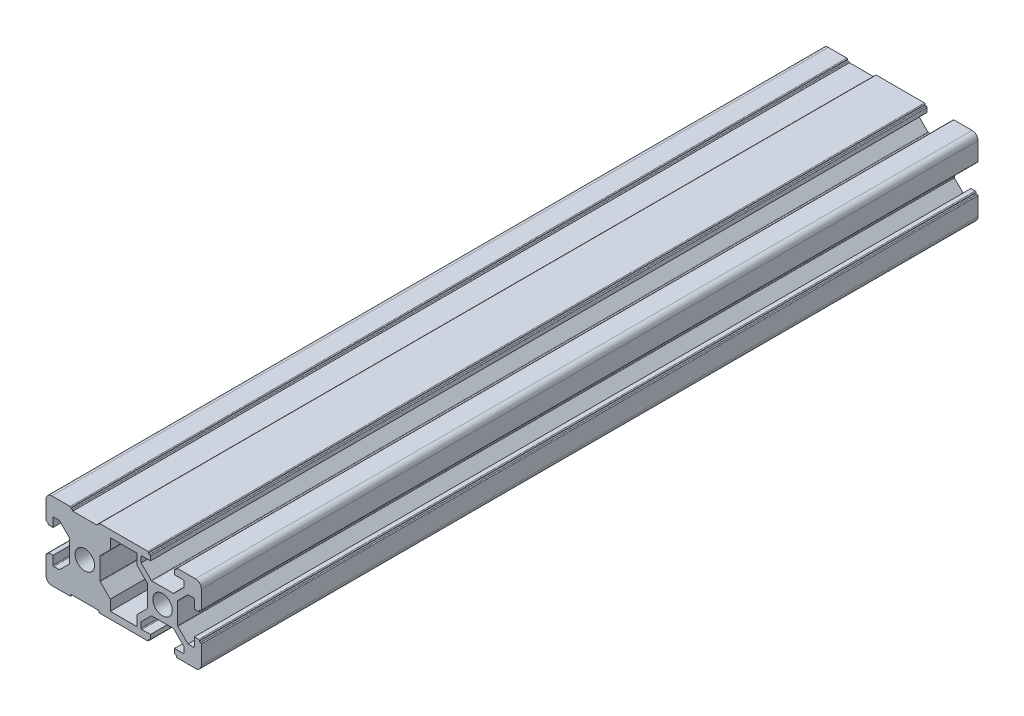
SolidWorks part; units mm, degrees
ref_plane "前视基准面" through (0, 0, 0) normal (0, 0, 1) x (1, 0, 0)
ref_plane "上视基准面" through (0, 0, 0) normal (0, 1, 0) x (1, 0, 0)
ref_plane "右视基准面" through (0, 0, 0) normal (1, 0, 0) x (0, 0, -1)
sketch "Sketch1" plane through (0, 0, 0) normal (0, 0, 1) x (1, 0, 0)
  line L0 (-8.5, 10) -> (-3.8, 10)
  line L3 (-8.5, -10) -> (-3.8, -10)
  line L5 (-10, 8.5) -> (-10, 3.8)
  line L10 (3.9, 2.7565) -> (3.9, -2.7565)
  line L11 (-3.9, 2.7565) -> (-3.9, -2.7565)
  line L12 (-3.9586, -2.8979) -> (-6.5607, -5.5)
  line L13 (3.6, 9.7) -> (3.6, 9.8)
  line L21 (-3.4, -9.5) -> (-3.3, -9.5)
  line L22 (3.8, -10) -> (8.5, -10)
  line L23 (3.3, -9.5) -> (3.4, -9.5)
  line L24 (-3.6, -9.7) -> (-3.6, -9.8)
  line L25 (3.6, -9.7) -> (3.6, -9.8)
  line L26 (-6.5607, -5.5) -> (-8, -5.5)
  line L27 (-9.7, -3.6) -> (-9.8, -3.6)
  line L28 (-9.5, -3.4) -> (-9.5, -3.3)
  line L29 (-8.2, -3.1) -> (-9.3, -3.1)
  line L30 (-8.2, -5.3) -> (-8.2, -3.1)
  line L31 (-10, -3.8) -> (-10, -8.5)
  line L33 (3.8, 10) -> (8.5, 10)
  line L40 (3.9586, -2.8979) -> (6.5607, -5.5)
  line L41 (3.3, 9.5) -> (3.4, 9.5)
  line L42 (30, 8.5) -> (30, 3.8)
  line L52 (3.9586, 2.8979) -> (6.5607, 5.5)
  line L53 (-3.6, 9.7) -> (-3.6, 9.8)
  line L54 (-3.4, 9.5) -> (-3.3, 9.5)
  line L59 (-9.5, 3.4) -> (-9.5, 3.3)
  line L60 (-9.7, 3.6) -> (-9.8, 3.6)
  line L61 (-8.2, 3.1) -> (-9.3, 3.1)
  line L62 (-8.2, 5.3) -> (-8.2, 3.1)
  line L63 (-6.5607, 5.5) -> (-8, 5.5)
  line L64 (-3.9586, 2.8979) -> (-6.5607, 5.5)
  line L65 (29.7, 3.6) -> (29.8, 3.6)
  line L66 (29.5, 3.4) -> (29.5, 3.3)
  line L67 (28.2, 3.1) -> (29.3, 3.1)
  line L68 (28.2, 5.3) -> (28.2, 3.1)
  line L69 (26.5607, 5.5) -> (28, 5.5)
  line L70 (23.9586, 2.8979) -> (26.5607, 5.5)
  line L71 (23.9, 2.7565) -> (23.9, -2.7565)
  line L72 (23.9586, -2.8979) -> (26.5607, -5.5)
  line L73 (26.5607, -5.5) -> (28, -5.5)
  line L74 (28.2, -5.3) -> (28.2, -3.1)
  line L75 (28.2, -3.1) -> (29.3, -3.1)
  line L76 (29.5, -3.4) -> (29.5, -3.3)
  line L77 (29.7, -3.6) -> (29.8, -3.6)
  line L78 (30, -3.8) -> (30, -8.5)
  line L79 (28.5, -10) -> (23.8, -10)
  line L80 (23.6, -9.7) -> (23.6, -9.8)
  line L81 (23.4, -9.5) -> (23.3, -9.5)
  line L82 (23.1, -8.2) -> (23.1, -9.3)
  line L83 (25.3, -8.2) -> (23.1, -8.2)
  line L84 (25.5, -6.5607) -> (25.5, -8)
  line L85 (22.8979, -3.9586) -> (25.5, -6.5607)
  line L86 (22.7565, -3.9) -> (17.2435, -3.9)
  line L87 (17.1021, -3.9586) -> (14.5, -6.5607)
  line L88 (14.5, -6.5607) -> (14.5, -8)
  line L89 (16.9, -8.2) -> (14.7, -8.2)
  line L90 (16.9, -8.2) -> (16.9, -9.3)
  line L91 (16.7, -9.5) -> (16.6, -9.5)
  line L92 (16.4, -9.7) -> (16.4, -9.8)
  line L93 (16.2, -10) -> (11.5, -10)
  line L94 (13.4393, 5.5) -> (13.4393, 8.2)
  line L96 (6.5607, 5.5) -> (6.5607, 8.2)
  line L97 (6.5607, 8.2) -> (13.4393, 8.2)
  line L99 (16.0414, -2.8979) -> (13.4393, -5.5)
  line L100 (16.1, 2.7565) -> (16.1, -2.7565)
  line L101 (16.0414, 2.8979) -> (13.4393, 5.5)
  line L107 (16.2, 10) -> (11.5, 10)
  line L108 (16.4, 9.7) -> (16.4, 9.8)
  line L109 (16.7, 9.5) -> (16.6, 9.5)
  line L110 (16.9, 8.2) -> (16.9, 9.3)
  line L111 (16.9, 8.2) -> (14.7, 8.2)
  line L112 (14.5, 6.5607) -> (14.5, 8)
  line L113 (17.1021, 3.9586) -> (14.5, 6.5607)
  line L114 (22.7565, 3.9) -> (17.2435, 3.9)
  line L115 (22.8979, 3.9586) -> (25.5, 6.5607)
  line L116 (25.5, 6.5607) -> (25.5, 8)
  line L117 (25.3, 8.2) -> (23.1, 8.2)
  line L118 (23.1, 8.2) -> (23.1, 9.3)
  line L119 (23.4, 9.5) -> (23.3, 9.5)
  line L120 (23.6, 9.7) -> (23.6, 9.8)
  line L121 (28.5, 10) -> (23.8, 10)
  line L122 (13.4393, -5.5) -> (13.4393, -8.2)
  line L124 (6.5607, -5.5) -> (6.5607, -8.2)
  line L125 (6.5607, -8.2) -> (13.4393, -8.2)
  line L127 (8.5, 10) -> (11.5, 10)
  line L128 (8.5, -10) -> (11.5, -10)
  line L129 (-3.3, -9.5) -> (3.3, -9.5)
  line L130 (-3.1, 9.3) -> (3.1, 9.3)
  arc A3 (-8.5, -10) -> (-10, -8.5) centre (-8.5, -8.5) cw
  arc A4 (-10, 8.5) -> (-8.5, 10) centre (-8.5, 8.5) cw
  arc A5 (3.4, -9.5) -> (3.6, -9.7) centre (3.4, -9.7) cw
  arc A6 (3.8, -10) -> (3.6, -9.8) centre (3.8, -9.8) cw
  arc A9 (-3.9, -2.7565) -> (-3.9586, -2.8979) centre (-4.1, -2.7565) cw
  arc A10 (-3.9, 2.7565) -> (-3.9586, 2.8979) centre (-4.1, 2.7565) ccw
  arc A13 (3.9586, 2.8979) -> (3.9, 2.7565) centre (4.1, 2.7565) ccw
  arc A14 (3.9, -2.7565) -> (3.9586, -2.8979) centre (4.1, -2.7565) ccw
  arc A17 (-3.6, -9.8) -> (-3.8, -10) centre (-3.8, -9.8) cw
  arc A19 (-3.6, -9.7) -> (-3.4, -9.5) centre (-3.4, -9.7) cw
  arc A20 (-8.2, 5.3) -> (-8, 5.5) centre (-8, 5.3) cw
  arc A23 (-8.2, -5.3) -> (-8, -5.5) centre (-8, -5.3) ccw
  arc A31 (3.1, 9.3) -> (3.3, 9.5) centre (3.3, 9.3) cw
  arc A32 (3.6, 9.8) -> (3.8, 10) centre (3.8, 9.8) cw
  arc A33 (3.6, 9.7) -> (3.4, 9.5) centre (3.4, 9.7) cw
  arc A34 (-3.8, 10) -> (-3.6, 9.8) centre (-3.8, 9.8) cw
  arc A35 (-3.3, 9.5) -> (-3.1, 9.3) centre (-3.3, 9.3) cw
  arc A36 (-3.4, 9.5) -> (-3.6, 9.7) centre (-3.4, 9.7) cw
  arc A39 (-10, 3.8) -> (-9.8, 3.6) centre (-9.8, 3.8) ccw
  arc A40 (-9.5, 3.3) -> (-9.3, 3.1) centre (-9.3, 3.3) ccw
  arc A41 (-9.7, 3.6) -> (-9.5, 3.4) centre (-9.7, 3.4) cw
  arc A42 (-10, -3.8) -> (-9.8, -3.6) centre (-9.8, -3.8) cw
  arc A43 (-9.5, -3.3) -> (-9.3, -3.1) centre (-9.3, -3.3) cw
  arc A44 (-9.5, -3.4) -> (-9.7, -3.6) centre (-9.7, -3.4) cw
  arc A45 (30, 8.5) -> (28.5, 10) centre (28.5, 8.5) ccw
  arc A46 (30, 3.8) -> (29.8, 3.6) centre (29.8, 3.8) cw
  arc A47 (29.7, 3.6) -> (29.5, 3.4) centre (29.7, 3.4) ccw
  arc A48 (29.5, 3.3) -> (29.3, 3.1) centre (29.3, 3.3) cw
  arc A49 (28.2, 5.3) -> (28, 5.5) centre (28, 5.3) ccw
  arc A50 (23.9, 2.7565) -> (23.9586, 2.8979) centre (24.1, 2.7565) cw
  arc A51 (23.9, -2.7565) -> (23.9586, -2.8979) centre (24.1, -2.7565) ccw
  arc A52 (28.2, -5.3) -> (28, -5.5) centre (28, -5.3) cw
  arc A53 (29.5, -3.3) -> (29.3, -3.1) centre (29.3, -3.3) ccw
  arc A54 (29.5, -3.4) -> (29.7, -3.6) centre (29.7, -3.4) ccw
  arc A55 (30, -3.8) -> (29.8, -3.6) centre (29.8, -3.8) ccw
  arc A56 (28.5, -10) -> (30, -8.5) centre (28.5, -8.5) ccw
  arc A57 (23.6, -9.8) -> (23.8, -10) centre (23.8, -9.8) ccw
  arc A58 (23.6, -9.7) -> (23.4, -9.5) centre (23.4, -9.7) ccw
  arc A59 (23.3, -9.5) -> (23.1, -9.3) centre (23.3, -9.3) cw
  arc A60 (25.3, -8.2) -> (25.5, -8) centre (25.3, -8) ccw
  arc A61 (22.8979, -3.9586) -> (22.7565, -3.9) centre (22.7565, -4.1) ccw
  arc A62 (17.2435, -3.9) -> (17.1021, -3.9586) centre (17.2435, -4.1) ccw
  arc A63 (14.7, -8.2) -> (14.5, -8) centre (14.7, -8) cw
  arc A64 (16.7, -9.5) -> (16.9, -9.3) centre (16.7, -9.3) ccw
  arc A65 (16.6, -9.5) -> (16.4, -9.7) centre (16.6, -9.7) ccw
  arc A66 (16.2, -10) -> (16.4, -9.8) centre (16.2, -9.8) ccw
  arc A72 (16.1, -2.7565) -> (16.0414, -2.8979) centre (15.9, -2.7565) cw
  arc A73 (16.0414, 2.8979) -> (16.1, 2.7565) centre (15.9, 2.7565) cw
  arc A79 (16.4, 9.8) -> (16.2, 10) centre (16.2, 9.8) ccw
  arc A80 (16.4, 9.7) -> (16.6, 9.5) centre (16.6, 9.7) ccw
  arc A81 (16.9, 9.3) -> (16.7, 9.5) centre (16.7, 9.3) ccw
  arc A82 (14.5, 8) -> (14.7, 8.2) centre (14.7, 8) cw
  arc A83 (17.2435, 3.9) -> (17.1021, 3.9586) centre (17.2435, 4.1) cw
  arc A84 (22.7565, 3.9) -> (22.8979, 3.9586) centre (22.7565, 4.1) ccw
  arc A85 (25.5, 8) -> (25.3, 8.2) centre (25.3, 8) ccw
  arc A86 (23.3, 9.5) -> (23.1, 9.3) centre (23.3, 9.3) ccw
  arc A87 (23.4, 9.5) -> (23.6, 9.7) centre (23.4, 9.7) ccw
  arc A88 (23.8, 10) -> (23.6, 9.8) centre (23.8, 9.8) ccw
  point P11 (3.9, 3.9)
  point P19 (3.3697, 4.4303)
  point P20 (-10.6428, -10.6428)
  point P25 (-11.1731, -10.1124)
  point P26 (4.4303, 3.3697)
  point P28 (-10.1124, -11.1731)
  dimension "D3" = 0.2
  dimension "D4" = 0.2
  dimension "D8" = 0.2
  dimension "D9" = 0.2
  dimension "D10" = 0.2
  dimension "D7" = 0.5
extrude "Boss-Extrude1" add sketch "Sketch1" along normal blind 200
ref_plane "hole" through (0, 0, 200) normal (0, 0, 1) x (1, 0, 0)
sketch "Sketch2" plane through (0, 0, 200) normal (0, 0, 1) x (1, 0, 0)
  circle A0 centre (0, 0) radius 2.5
  circle A1 centre (20, 0) radius 2.5
  dimension "D1" = 5
extrude "Cut-Extrude1" cut sketch "Sketch2" against normal through all
